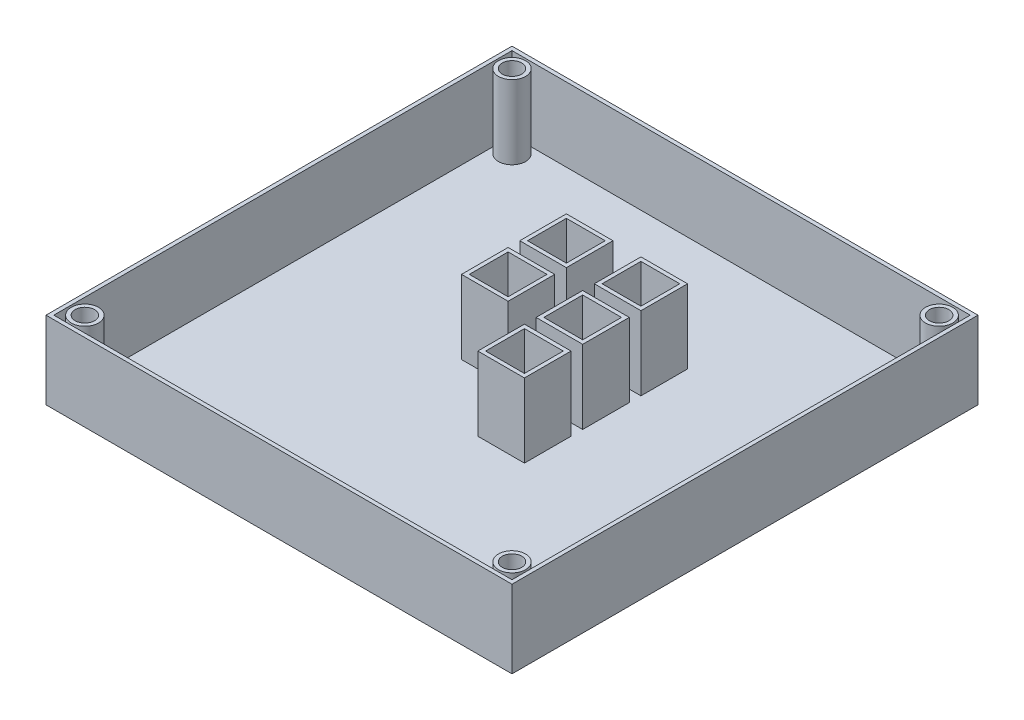
SolidWorks part; units mm, degrees
ref_plane "Front Plane" through (0, 0, 0) normal (0, 0, 1) x (1, 0, 0)
ref_plane "Top Plane" through (0, 0, 0) normal (0, 1, 0) x (1, 0, 0)
ref_plane "Right Plane" through (0, 0, 0) normal (1, 0, 0) x (0, 0, -1)
sketch "Sketch1" plane through (0, 0, 0) normal (0, 1, 0) x (1, 0, 0)
  line L1 (77.4843, 101.0292) -> (-74.9157, 101.0292)
  line L2 (77.4843, 101.0292) -> (77.4843, -51.3708)
  line L3 (77.4843, -51.3708) -> (-74.9157, -51.3708)
  line L4 (-74.9157, 101.0292) -> (-74.9157, -51.3708)
  line L5 (77.4843, 101.0292) -> (-74.9157, -51.3708) construction
  line L6 (77.4843, -51.3708) -> (-74.9157, 101.0292) construction
  point P0 (1.2843, 24.8292)
  dimension "D1" = 152.4
  dimension "D2" = 152.4
extrude "Boss-Extrude1" add sketch "Sketch1" along normal blind 25.4
sketch "Sketch3" plane through (0, 25.4, 0) normal (0, 1, 0) x (1, 0, 0)
  line L0 (77.4843, 101.0292) -> (-74.9157, 101.0292) construction
  line L1 (-74.9157, 101.0292) -> (-74.9157, -51.3708) construction
  line L2 (77.4843, -51.3708) -> (77.4843, 101.0292) construction
  line L3 (-74.9157, -51.3708) -> (77.4843, -51.3708) construction
  circle A0 centre (-68.5657, 94.6792) radius 3.175
  circle A1 centre (71.1343, 94.6792) radius 3.175
  circle A2 centre (-68.5657, -45.0208) radius 3.175
  circle A3 centre (71.1343, -45.0208) radius 3.175
  dimension "D1" = 6.35
  dimension "D2" = 6.35
  dimension "D3" = 6.35
  dimension "D4" = 6.35
  dimension "D5" = 6.35
  dimension "D6" = 6.35
  dimension "D7" = 6.35
  dimension "D8" = 6.35
extrude "Cut-Extrude1" cut sketch "Sketch3" against normal through all
sketch "Sketch4" plane through (0, 25.4, 0) normal (0, 1, 0) x (1, 0, 0)
  line L0 (7.1263, 61.1512) -> (7.1263, -11.4928)
  line L1 (-4.5577, 61.1512) -> (-4.5577, -11.4928)
  line L2 (-17.2577, 42.1012) -> (19.8263, 42.1012)
  line L3 (19.8263, 48.4512) -> (-17.2577, 48.4512)
  line L4 (-17.2577, 29.4012) -> (19.8263, 29.4012)
  line L5 (-17.2577, 23.0512) -> (19.8263, 23.0512)
  line L6 (-17.2577, 10.3512) -> (20.2693, 10.3512)
  line L7 (-17.2577, 61.1512) -> (19.8263, 61.1512)
  line L8 (-17.2577, 61.1512) -> (-17.2577, -11.4928)
  line L9 (-17.2577, -11.4928) -> (19.8263, -11.4928)
  line L10 (19.8263, 61.1512) -> (19.8263, -11.4928)
  line L11 (-17.2577, 61.1512) -> (19.8263, -11.4928) construction
  line L12 (-17.2577, -11.4928) -> (19.8263, 61.1512) construction
  point P12 (1.2843, 24.8292)
  dimension "D1" = 72.644
  dimension "D2" = 37.084
  dimension "D3" = 12.7
  dimension "D4" = 12.7
  dimension "D5" = 12.7
  dimension "D6" = 6.35
  dimension "D7" = 12.7
  dimension "D8" = 6.35
  dimension "D9" = 12.7
extrude "Cut-Extrude2" cut sketch "Sketch4" against normal through all contours L7 L8 L3 L1 | L10 L7 L0 L3 | L2 L8 L4 L1 | L10 L2 L0 L4 | L10 L5 L0 L6
shell "Shell1" thickness 1.27
